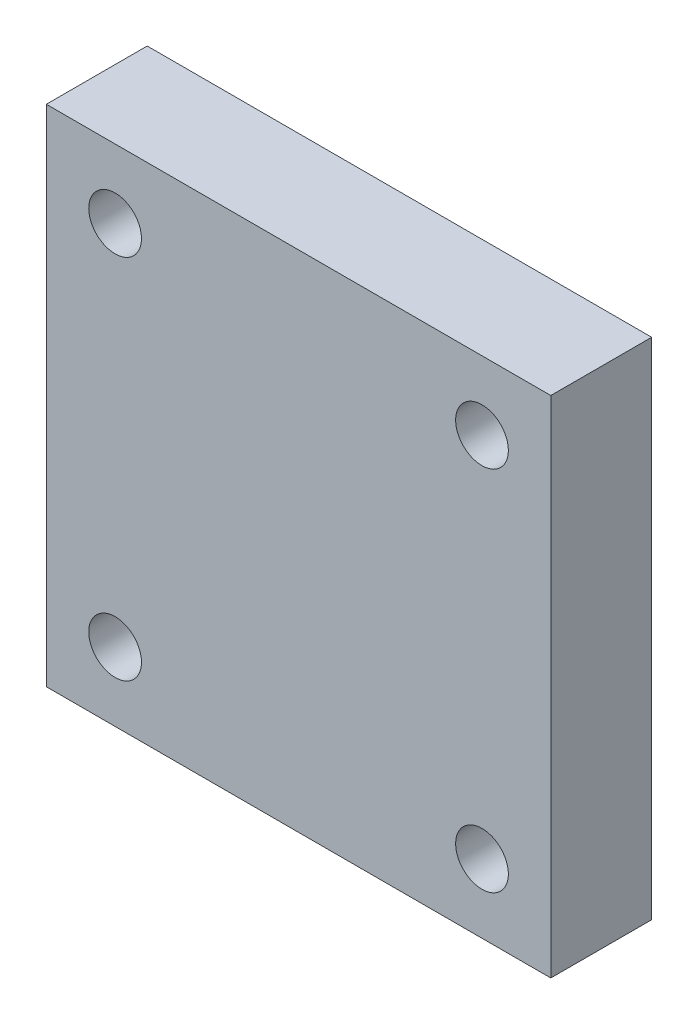
SolidWorks part; units mm, degrees
ref_plane "Front Plane" through (0, 0, 0) normal (1, 0, 0) x (0, 1, 0)
ref_plane "Top Plane" through (0, 0, 0) normal (0, 0, 1) x (0, 1, 0)
ref_plane "Right Plane" through (0, 0, 0) normal (0, 1, 0) x (-1, 0, 0)
sketch "Sketch1" plane through (0, 0, 0) normal (0, 0, 1) x (0, 1, 0)
  line L0 (0, 13.97) -> (0, -13.97) construction
  line L1 (13.97, -13.97) -> (-13.97, -13.97)
  line L2 (13.97, -13.97) -> (13.97, 13.97)
  line L3 (13.97, 13.97) -> (-13.97, 13.97)
  line L4 (-13.97, -13.97) -> (-13.97, 13.97)
  line L5 (13.97, -13.97) -> (-13.97, 13.97) construction
  line L6 (13.97, 13.97) -> (-13.97, -13.97) construction
  line L7 (-13.97, 0) -> (13.97, 0) construction
  circle A0 centre (-10.16, 10.16) radius 1.4605
  circle A1 centre (10.16, 10.16) radius 1.4605
  circle A2 centre (-10.16, -10.16) radius 1.4605
  circle A3 centre (10.16, -10.16) radius 1.4605
  point P0 (0, 0)
  dimension "D3" = 2.921
  dimension "D1" = 27.94
  dimension "D2" = 20.32
extrude "Boss-Extrude1" add sketch "Sketch1" along normal blind 5.588
